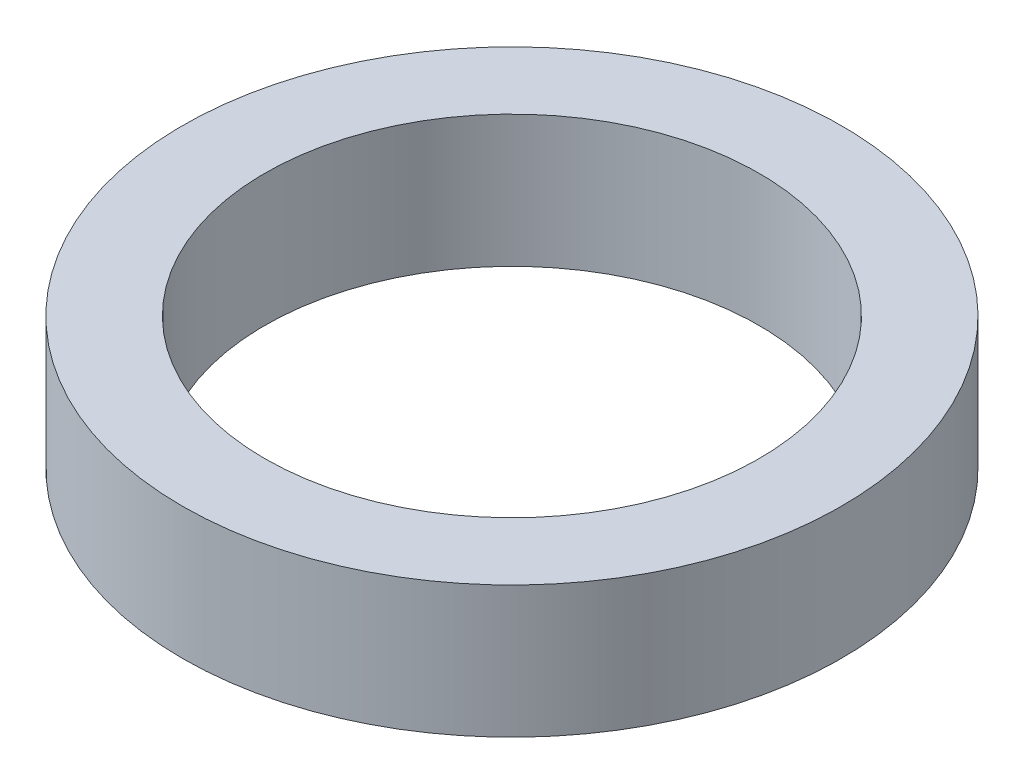
SolidWorks part; units mm, degrees
ref_plane "Front Plane" through (0, 0, 0) normal (0, 0, 1) x (1, 0, 0)
ref_plane "Top Plane" through (0, 0, 0) normal (0, 1, 0) x (1, 0, 0)
ref_plane "Right Plane" through (0, 0, 0) normal (1, 0, 0) x (0, 0, -1)
sketch "Sketch1" plane through (0, 0, 0) normal (0, 1, 0) x (1, 0, 0)
  circle A0 centre (0, 0) radius 4.7625
  circle A1 centre (0, 0) radius 6.35
  dimension "D1" = 9.525
  dimension "D2" = 12.7
extrude "Boss-Extrude1" add sketch "Sketch1" along normal blind 2.54
